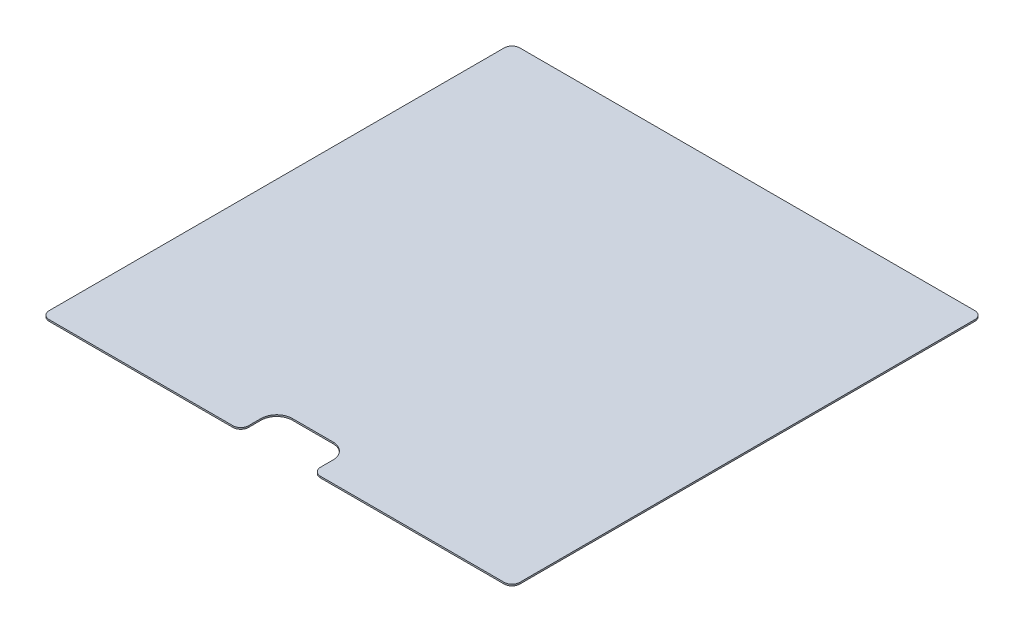
SolidWorks part; units mm, degrees
ref_plane "Front Plane" through (0, 0, 0) normal (0, 0, 1) x (1, 0, 0)
ref_plane "Top Plane" through (0, 0, 0) normal (0, 1, 0) x (1, 0, 0)
ref_plane "Right Plane" through (0, 0, 0) normal (1, 0, 0) x (0, 0, -1)
sketch "Sketch1" plane through (0, 0, 0) normal (0, 1, 0) x (1, 0, 0)
  line L0 (2.2929, -14.5) -> (2.2929, -13.7071)
  line L1 (14.5, -15) -> (2.7929, -15)
  line L2 (15, -14.5) -> (15, 14.5)
  line L3 (14.5, 15) -> (-14.5, 15)
  line L4 (-15, -14.5) -> (-15, 14.5)
  line L5 (15, -15) -> (-15, 15) construction
  line L6 (15, 15) -> (-15, -15) construction
  line L7 (1.2929, -12.7071) -> (-1.2929, -12.7071)
  line L8 (-2.2929, -13.7071) -> (-2.2929, -14.5)
  line L9 (-2.7929, -15) -> (-14.5, -15)
  arc A0 (-14.5, 15) -> (-15, 14.5) centre (-14.5, 14.5) ccw
  arc A1 (15, 14.5) -> (14.5, 15) centre (14.5, 14.5) ccw
  arc A2 (-14.5, -15) -> (-15, -14.5) centre (-14.5, -14.5) cw
  arc A3 (14.5, -15) -> (15, -14.5) centre (14.5, -14.5) ccw
  arc A4 (-2.2929, -14.5) -> (-2.7929, -15) centre (-2.7929, -14.5) cw
  arc A5 (2.2929, -14.5) -> (2.7929, -15) centre (2.7929, -14.5) ccw
  arc A6 (-1.2929, -12.7071) -> (-2.2929, -13.7071) centre (-1.2929, -13.7071) ccw
  arc A7 (2.2929, -13.7071) -> (1.2929, -12.7071) centre (1.2929, -13.7071) ccw
  point P0 (0, 0)
  point P9 (0, -12.7071)
  dimension "D2" = 0.5
  dimension "D3" = 0.5
  dimension "D4" = 1
  dimension "D1" = 30
extrude "Boss-Extrude1" add sketch "Sketch1" along normal mid plane 0.1
